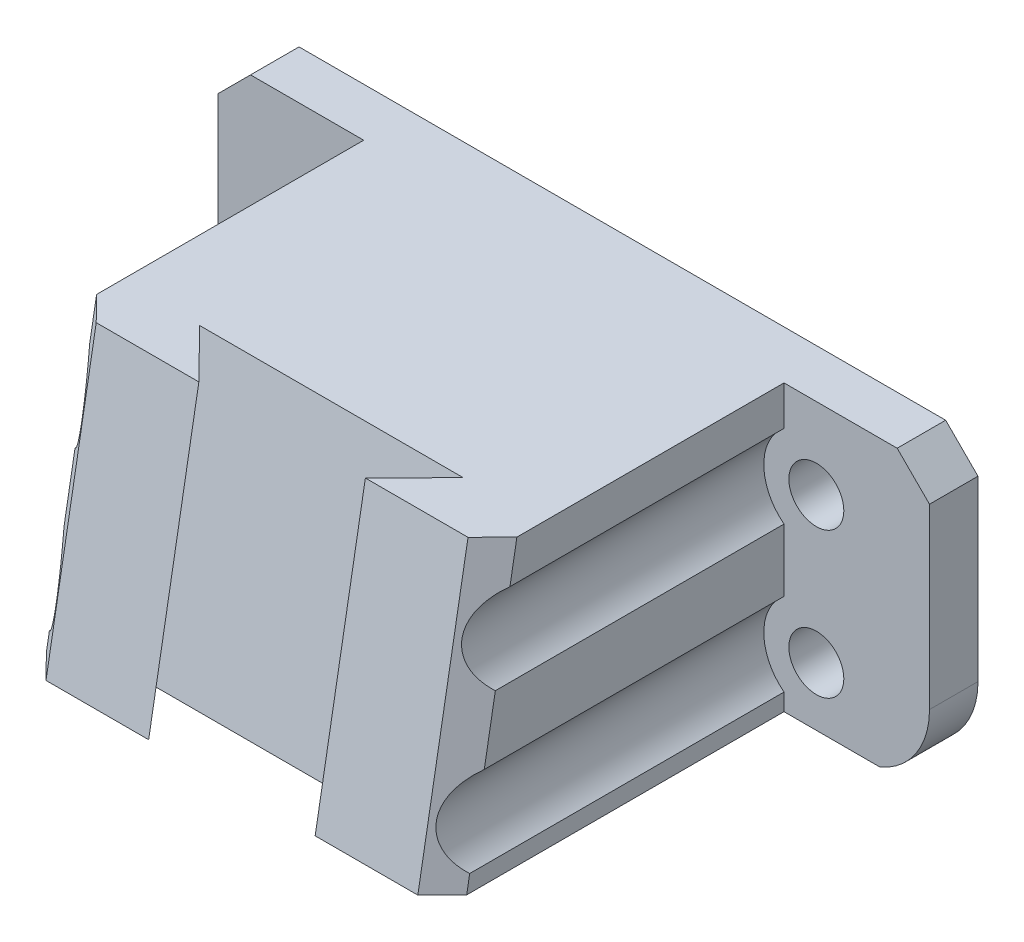
SolidWorks part; units mm, degrees
ref_plane "Front Plane" through (0, 0, 0) normal (0, 0, 1) x (1, 0, 0)
ref_plane "Top Plane" through (0, 0, 0) normal (0, 1, 0) x (1, 0, 0)
ref_plane "Right Plane" through (0, 0, 0) normal (1, 0, 0) x (0, 0, -1)
sketch "Sketch1" plane through (0, 0, 0) normal (0, 0, 1) x (1, 0, 0)
  line L0 (-40.9231, -5.1154) -> (-3.0769, -5.1154)
  line L10 (-36, -12.5) -> (-36, -26.7094)
  line L11 (-35.4388, -29.0109) -> (-31.3992, -36.8016)
  line L12 (-26.9604, -39.5) -> (-17.0396, -39.5)
  line L13 (-12.6008, -36.8016) -> (-8.5612, -29.0109)
  line L14 (-8, -26.7094) -> (-8, -12.5)
  line L15 (0, -0.5) -> (0, 10.5)
  line L16 (0, 10.5) -> (-2, 12.5)
  line L17 (-2, 12.5) -> (-42, 12.5)
  line L18 (-42, 12.5) -> (-44, 10.5)
  line L19 (-44, 10.5) -> (-44, -0.5)
  line L25 (0, -0.5) -> (0, 10.5)
  line L26 (0, 10.5) -> (-2, 12.5)
  line L27 (-2, 12.5) -> (-42, 12.5)
  line L28 (-42, 12.5) -> (-44, 10.5)
  line L29 (-44, 10.5) -> (-44, -0.5)
  arc A8 (-36, -26.7094) -> (-35.4388, -29.0109) centre (-31, -26.7094) ccw
  arc A9 (-31.3992, -36.8016) -> (-26.9604, -39.5) centre (-26.9604, -34.5) ccw
  arc A10 (-17.0396, -39.5) -> (-12.6008, -36.8016) centre (-17.0396, -34.5) ccw
  arc A11 (-8.5612, -29.0109) -> (-8, -26.7094) centre (-13, -26.7094) ccw
  arc A12 (-3.0769, -5.1154) -> (-8, -12.5) centre (0, -12.5) ccw
  arc A13 (-3.0769, -5.1154) -> (0, -0.5) centre (-5, -0.5) ccw
  arc A14 (-44, -0.5) -> (-40.9231, -5.1154) centre (-39, -0.5) ccw
  arc A15 (-36, -12.5) -> (-40.9231, -5.1154) centre (-44, -12.5) ccw
  arc A21 (-3.0769, -5.1154) -> (0, -0.5) centre (-5, -0.5) ccw
  arc A22 (-44, -0.5) -> (-40.9231, -5.1154) centre (-39, -0.5) ccw
  dimension "D1" = 0
extrude "Boss-Extrude1" add sketch "Sketch1" along normal blind 3
sketch "Sketch2" plane through (0, 0, 3) normal (0, 0, 1) x (1, 0, 0)
  point P0 (-37, 7.5)
  point P1 (-37, -1.5)
  point P3 (-7, 7.5)
  point P5 (-7, -1.5)
hole_wizard "M3 Clearance Hole1" positions "Sketch2" profile "Sketch3" hole size "M3" standard "ISO" end condition up to next
sketch "Sketch3" plane through (-37, 7.5, 3) normal (1, 0, 0) x (0, -1, 0)
  line L0 (0, 0) -> (0, 3)
  line L1 (0, 3) -> (1.7, 3)
  line L2 (1.7, 3) -> (1.7, 0)
  line L5 (1.7, 0) -> (0, 0)
  line L11 (0, -6.35) -> (0, 107.95) construction
  dimension "Thru Hole Dia." = 3.4
  dimension "Thru Hole Depth" = 3
ref_plane "Plane1" through (-22, 0, 0) normal (1, 0, 0) x (0, 0, -1)
sketch "Sketch5" plane through (-22, 0, 0) normal (1, 0, 0) x (0, 0, -1)
  line L0 (-18, 12.5) -> (-21.1061, -5.1154)
  line L1 (-21.1061, -5.1154) -> (-3, -5.1154)
  line L2 (-3, -5.1154) -> (-3, 12.5)
  line L3 (-3, 12.5) -> (-18, 12.5)
  line L4 (-3, 10.5) -> (-3, 12.5) construction
  line L5 (-3, 12.5) -> (0, 12.5) construction
  dimension "D1" = 15
  dimension "D2" = 80
extrude "Boss-Extrude3" add sketch "Sketch5" along normal blind 13 and the other way blind 13
ref_plane "Plane2" through (0, 0.2372, -0.0418) normal (0, 0.9848, -0.1736) x (1, 0, 0)
sketch "Sketch6" plane through (0, 0.2372, -0.0418) normal (0, 0.9848, -0.1736) x (1, 0, 0)
  line L1 (-35, -19.8971) -> (-35, -21.3971)
  line L2 (-35, -21.3971) -> (-33.5, -22.8971)
  line L3 (-33.5, -22.8971) -> (-27.15, -22.8971)
  line L4 (-27.15, -22.8971) -> (-30.15, -19.8971)
  line L6 (-13.85, -19.8971) -> (-16.85, -22.8971)
  line L7 (-16.85, -22.8971) -> (-10.5, -22.8971)
  line L8 (-10.5, -22.8971) -> (-9, -21.3971)
  line L9 (-9, -21.3971) -> (-9, -19.8971)
  line L10 (-27.15, -22.8971) -> (-16.85, -22.8971) construction
  line L11 (-30.15, -19.8971) -> (-35, -19.8971)
  line L12 (-13.85, -19.8971) -> (-9, -19.8971)
  line L13 (-35, -19.8971) -> (-9, -19.8971) construction
  point P1 (-22, -22.8971)
  point P14 (-22, -19.8971)
  dimension "D1" = 16.3
  dimension "D2" = 3
  dimension "D3" = 45
  dimension "D4" = 26
  dimension "D5" = 1.5
  dimension "D6" = 1.5
  dimension "D7" = 45
extrude "Boss-Extrude4" add sketch "Sketch6" against normal up to surface and the other way up to surface up to face at (-22, -5.1154, 6.7765) other way up to face at (-22, 12.5, 6)
sketch "Sketch7" plane through (0, 0, 3) normal (0, 0, 1) x (1, 0, 0)
  circle A0 centre (-37, 7.5) radius 3.25
  circle A1 centre (-37, -1.5) radius 3.25
  circle A2 centre (-7, -1.5) radius 3.25
  circle A3 centre (-7, 7.5) radius 3.25
  point P0 (-37, 7.5)
  point P1 (-37, -1.5)
  point P3 (-7, -1.5)
  point P5 (-7, 7.5)
  dimension "D1" = 6.5
extrude "Cut-Extrude1" cut sketch "Sketch7" along normal up to next
